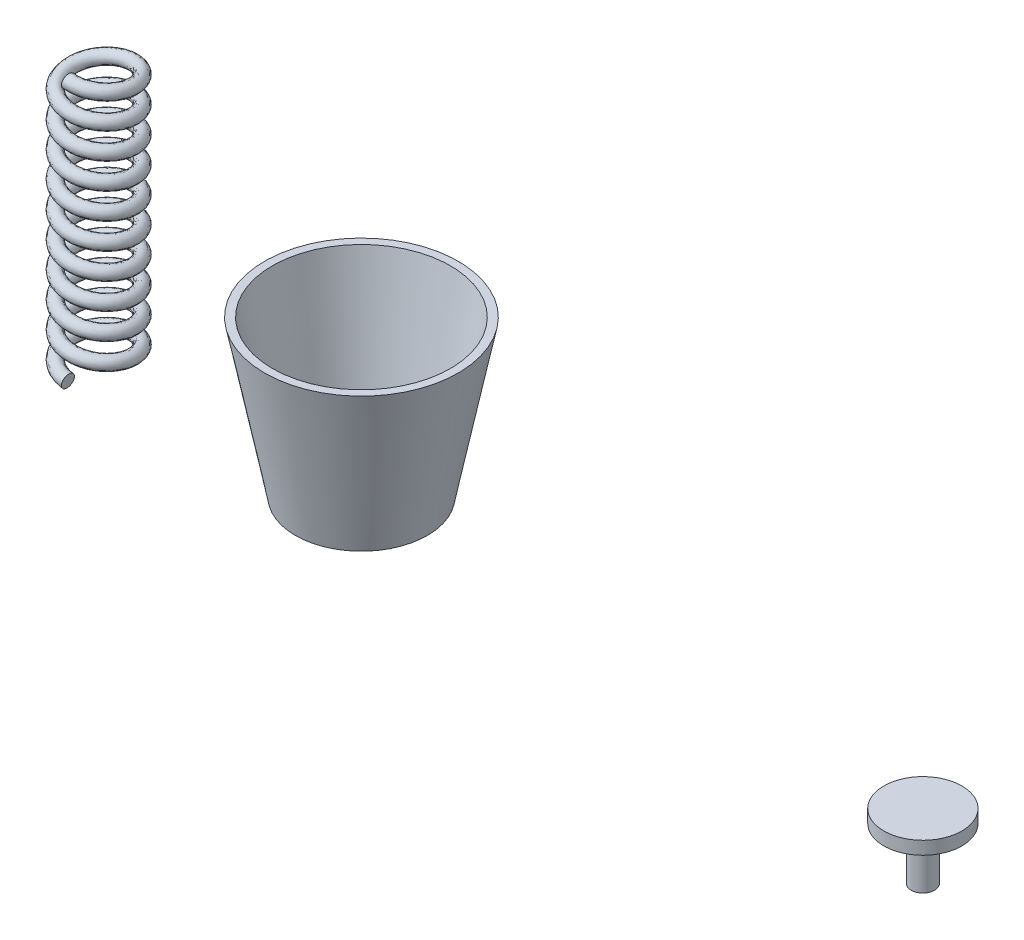
SolidWorks part; units mm, degrees
other "爆炸视图1"
other "爆炸步骤1"
other "爆炸直线1"
other "爆炸步骤2"
other "爆炸直线1"
ref_plane "前视基准面" through (0, 0, 0) normal (0, 0, 1) x (1, 0, 0)
ref_plane "上视基准面" through (0, 0, 0) normal (0, 1, 0) x (1, 0, 0)
ref_plane "右视基准面" through (0, 0, 0) normal (1, 0, 0) x (0, 0, -1)
sketch "草图1" plane through (0, 0, 0) normal (0, 1, 0) x (1, 0, 0)
  circle A1 centre (40.4965, 6.9777) radius 11.8102
  dimension "D1" = 23.6205
curve "螺旋线/涡状线1" pitch 10 height 100 turns 10
sweep "扫描1" add path "螺旋线/涡状线1" circular profile diameter 5 parameters "D3"=5
sketch "草图18" plane through (0, 0, 0) normal (0, 0, 1) x (1, 0, 0)
  line L0 (148.4832, 12.8362) -> (173.8715, 12.8362)
  line L1 (173.8715, 12.8362) -> (185.707, 72.8362)
  line L2 (185.707, 72.8362) -> (182.707, 72.8362)
  line L3 (148.4832, 12.8362) -> (148.4832, 16.8362) construction
  line L4 (148.4832, 16.8362) -> (171.6605, 16.8362)
  line L5 (171.6605, 16.8362) -> (182.707, 72.8362)
  line L6 (148.4832, 16.8362) -> (148.4832, 12.8362)
  dimension "D1" = 3
  dimension "D2" = 60
  dimension "D3" = 4
  dimension "D4" = 101.159
  dimension "D5" = 25.3883
revolve "旋转2" add sketch "草图18" angle 360 about L6
sketch "草图19" plane through (0, 0, 0) normal (0, 0, 1) x (1, 0, 0)
  line L0 (278.5208, 47.964) -> (293.5208, 47.964)
  line L1 (278.5208, 47.964) -> (278.5208, 42.964)
  line L2 (278.5208, 42.964) -> (289.0208, 42.964)
  line L3 (289.0208, 42.964) -> (289.0208, 22.964)
  line L4 (289.0208, 22.964) -> (293.5208, 22.964)
  line L5 (293.5208, 22.964) -> (293.5208, 47.964)
  dimension "D1" = 15
  dimension "D2" = 4.5
  dimension "D3" = 5
  dimension "D4" = 25
revolve "旋转3" add sketch "草图19" angle 360 about L5
move or copy body "实体-移动/复制1" bodies to move or copy 108 copy no translate (0, -30.775, 0)
move or copy body "实体-移动/复制2" bodies to move or copy 109 copy no translate (70.7992, 0, 0)
